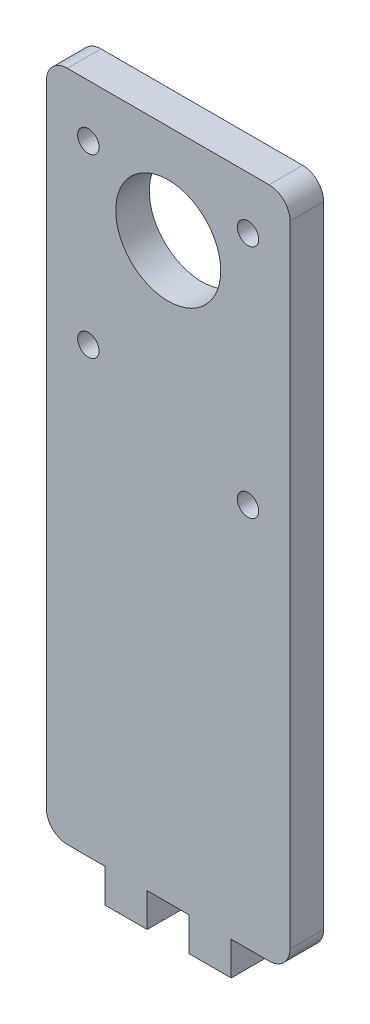
SolidWorks part; units mm, degrees
ref_plane "Front Plane" through (0, 0, 0) normal (0, 0, 1) x (1, 0, 0)
ref_plane "Top Plane" through (0, 0, 0) normal (0, 1, 0) x (1, 0, 0)
ref_plane "Right Plane" through (0, 0, 0) normal (1, 0, 0) x (0, 0, -1)
sketch "Sketch1" plane through (0, 0, 0) normal (0, 0, 1) x (1, 0, 0)
  line L1 (-29, -80) -> (29, -80)
  line L2 (-29, -80) -> (-29, 80)
  line L3 (-29, 80) -> (29, 80)
  line L4 (29, -80) -> (29, 80)
  line L5 (-29, -80) -> (29, 80) construction
  line L6 (-29, 80) -> (29, -80) construction
  point P0 (0, 0)
  dimension "D1" = 58
  dimension "D2" = 160
extrude "Boss-Extrude1" add sketch "Sketch1" along normal blind 8
sketch "Sketch2" plane through (0, 0, 8) normal (0, 0, 1) x (1, 0, 0)
  line L0 (-1011.6262, 67.5) -> (48988.3738, 67.5) construction
  line L1 (-1012.3101, 25.5) -> (48987.6899, 25.5) construction
  line L2 (-1012.3101, 11.5) -> (48987.6899, 11.5) construction
  line L3 (0, -1000) -> (0, 49000) construction
  line L4 (-19, -940.1593) -> (-19, 49059.8407) construction
  line L5 (19, -944.2626) -> (19, 49055.7374) construction
  line L6 (29, 80) -> (-29, 80) construction
  circle A0 centre (-19, 67.5) radius 2.55
  circle A1 centre (19, 67.5) radius 2.55
  circle A2 centre (-19, 25.5) radius 2.55
  circle A3 centre (19, 11.5) radius 2.55
  circle A4 centre (0, 56.5) radius 12.5
  dimension "D6" = 5.1
  dimension "D7" = 5.1
  dimension "D8" = 5.1
  dimension "D9" = 5.1
  dimension "D11" = 25
  dimension "D1" = 12.5
  dimension "D2" = 42
  dimension "D3" = 56
  dimension "D4" = 19
  dimension "D5" = 19
  dimension "D10" = 23.5
extrude "Cut-Extrude1" cut sketch "Sketch2" against normal through all
sketch "Sketch5" plane through (0, 0, 8) normal (0, 0, 1) x (1, 0, 0)
  circle A0 centre (-19, 67.5) radius 4.75
  circle A1 centre (19, 67.5) radius 4.75
  circle A2 centre (19, 11.5) radius 4.75
  circle A3 centre (-19, 25.5) radius 4.75
  dimension "D1" = 9.5
  dimension "D2" = 9.5
  dimension "D3" = 9.5
  dimension "D4" = 9.5
extrude "Cut-Extrude2" [suppressed] cut sketch "Sketch5" against normal blind 3
sketch "Sketch6" plane through (0, -80, 0) normal (0, -1, 0) x (1, 0, 0)
  line L0 (-29, 0) -> (29, 0) construction
  line L1 (-5, 0) -> (-15, 0)
  line L2 (-5, 0) -> (-5, 8)
  line L3 (-5, 8) -> (-15, 8)
  line L4 (-15, 0) -> (-15, 8)
  line L5 (-29, 8) -> (29, 8) construction
  line L11 (5, 0) -> (15, 0)
  line L12 (5, 0) -> (5, 8)
  line L13 (5, 8) -> (15, 8)
  line L14 (15, 0) -> (15, 8)
  dimension "D1" = 5
  dimension "D2" = 10
  dimension "D5" = 5
  dimension "D6" = 10
extrude "Boss-Extrude3" add sketch "Sketch6" along normal blind 8
fillet "Fillet2" radius 5 4 edges at (29, 80, 4) (-29, 80, 4) (29, -80, 4) (-29, -80, 4)
